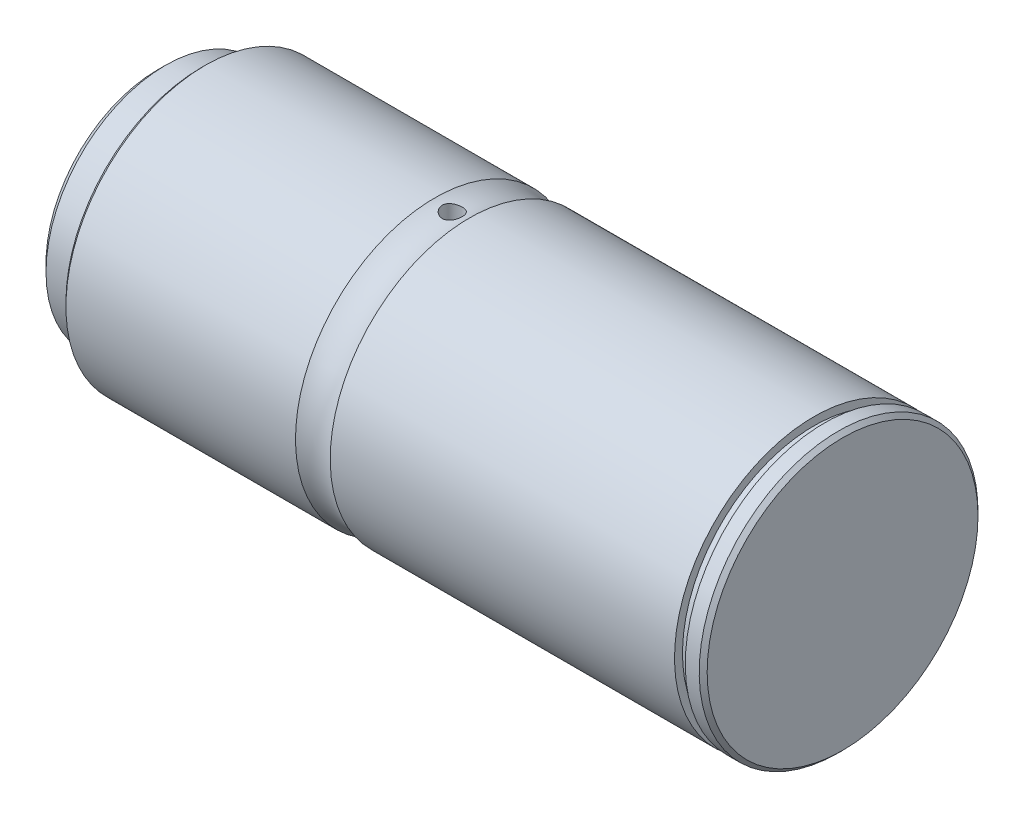
SolidWorks part; units mm, degrees
material "45"
ref_plane "前视基准面" through (0, 0, 0) normal (0, 0, 1) x (1, 0, 0)
ref_plane "上视基准面" through (0, 0, 0) normal (0, 1, 0) x (1, 0, 0)
ref_plane "右视基准面" through (0, 0, 0) normal (1, 0, 0) x (0, 0, -1)
sketch "草图1" plane through (0, 0, 0) normal (0, 0, 1) x (1, 0, 0)
  line L0 (0, 0) -> (172, 0)
  line L1 (0, 0) -> (344, 0) construction
  line L2 (0, 0) -> (0, 62.4896) construction
  line L3 (0, 0) -> (0, 30)
  line L4 (0, 30) -> (11, 30)
  line L5 (11, 30) -> (11, 35)
  line L6 (11, 35) -> (69.6411, 35)
  line L7 (164.8, 35) -> (78.3589, 35)
  line L8 (164.8, 35) -> (164.8, 33)
  line L9 (164.8, 33) -> (167.5, 33)
  line L10 (167.5, 33) -> (167.5, 35)
  line L11 (167.5, 35) -> (172, 35)
  line L13 (172, 35) -> (172, 0)
  arc A0 (69.6411, 35) -> (78.3589, 35) centre (74, 44) ccw
  dimension "D1" = 60
  dimension "D4" = 9
  dimension "D5" = 10
  dimension "D6" = 63
  dimension "D2" = 11
  dimension "D3" = 70
  dimension "D7" = 172
  dimension "D8" = 4.5
  dimension "D11" = 2.7
  dimension "D12" = 2
revolve "旋转1" add sketch "草图1" angle 360 about L1
sketch "草图2" plane through (0, 0, 0) normal (0, 1, 0) x (1, 0, 0)
  line L0 (0, 0) -> (162.6886, 0) construction
  line L1 (0, 30) -> (0, -30) construction
  circle A0 centre (74, 0) radius 2.5
  dimension "D1" = 74
  dimension "D2" = 5
extrude "切除-拉伸1" cut sketch "草图2" against normal mid plane 100
chamfer "倒角1" distance 2 angle 45 1 edges at (0, -30, 0)
chamfer "倒角2" distance 1 angle 45 1 edges at (11, -35, 0)
chamfer "倒角3" distance 1 angle 45 1 edges at (172, -35, 0)
sketch "草图3" plane through (0, 0, 0) normal (-1, 0, 0) x (0, 0, 1)
  circle A0 centre (0, 0) radius 15
  dimension "D1" = 30
extrude "切除-拉伸2" cut sketch "草图3" against normal blind 10
hole_wizard "Ø8.0 (8) 直径孔2" positions "草图5" profile "草图6" hole size "Ø8.0" standard "GB"
sketch "草图5" plane through (10, 0, 0) normal (-1, 0, 0) x (0, 0, 1)
  circle A0 centre (0, 0) radius 15 construction
  point P0 (0, 0)
sketch "草图6" plane through (10, 0, 0) normal (0, 1, 0) x (0, 0, 1)
  line L0 (0, 0) -> (0, 73.4034)
  line L1 (0, 73.4034) -> (4, 71)
  line L2 (4, 71) -> (4, 0)
  line L5 (4, 0) -> (0, 0)
  line L10 (0, 73.4034) -> (-4, 71) construction
  line L11 (0, -6.35) -> (0, 107.95) construction
  dimension "孔直径" = 8
  dimension "孔深度" = 71
  dimension "导头角度" = 118
hole_wizard "M10x1.0 螺纹孔2" positions "草图8" profile "草图9" tap size "M10x1.0" standard "GB"
sketch "草图8" plane through (10, 0, 0) normal (-1, 0, 0) x (0, 0, 1)
  circle A0 centre (0, 0) radius 15 construction
  point P0 (0, 0)
sketch "草图9" plane through (10, 0, 0) normal (0, 1, 0) x (0, 0, 1)
  line L0 (0, 0) -> (0, 22.7039)
  line L1 (0, 22.7039) -> (4.5, 20)
  line L2 (4.5, 20) -> (4.5, 0)
  line L5 (4.5, 0) -> (0, 0)
  line L10 (0, 22.7039) -> (-4.5, 20) construction
  line L11 (0, -6.35) -> (0, 107.95) construction
  dimension "螺纹孔钻头直径" = 9
  dimension "螺纹孔钻头深度" = 20
  dimension "导头角度" = 118
cosmetic thread "孔螺蚊线1" parameters "D1"=15, "D2"=10
